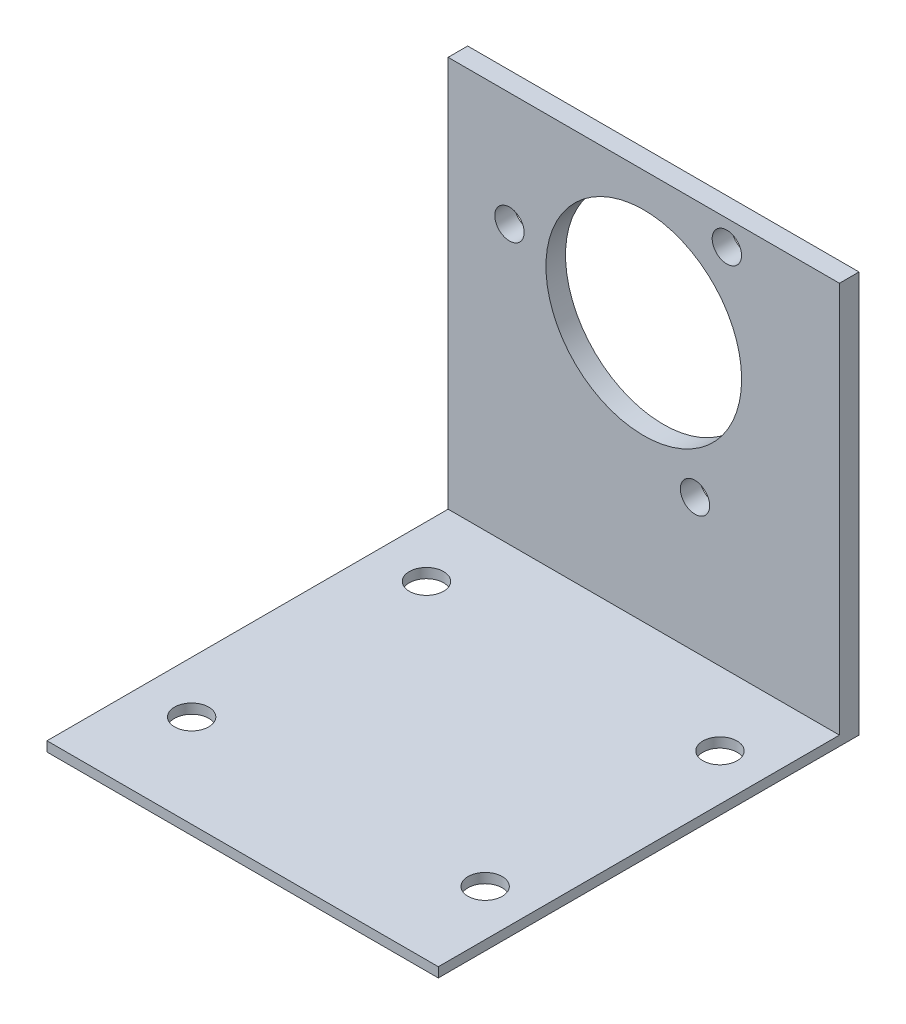
SolidWorks part; units mm, degrees
ref_plane "Front Plane" through (0, 0, 0) normal (0, 0, 1) x (1, 0, 0)
ref_plane "Top Plane" through (0, 0, 0) normal (0, 1, 0) x (1, 0, 0)
ref_plane "Right Plane" through (0, 0, 0) normal (1, 0, 0) x (0, 0, -1)
sketch "Sketch1" plane through (0, 0, 0) normal (0, 1, 0) x (1, 0, 0)
  line L0 (-20, 19.5) -> (20, 19.5)
  line L1 (-20, -21.5) -> (20, -21.5)
  line L2 (-20, -21.5) -> (-20, 21.5)
  line L3 (-20, 21.5) -> (20, 21.5)
  line L4 (20, -21.5) -> (20, 21.5)
  line L5 (-20, -21.5) -> (20, 21.5) construction
  line L6 (-20, 21.5) -> (20, -21.5) construction
  circle A7 centre (-14.7151, 12) radius 1.75
  circle A8 centre (15.2849, 12) radius 1.75
  circle A9 centre (-14.7151, -12) radius 1.75
  circle A10 centre (15.2849, -12) radius 1.75
  point P0 (0, 0)
  dimension "D4" = 30
  dimension "D5" = 3.5
  dimension "D6" = 3.5
  dimension "D7" = 24
  dimension "D8" = 9.5
  dimension "D9" = 5.2849
  dimension "D10" = 3.5
  dimension "D12" = 3.5
  dimension "D1" = 2
  dimension "D2" = 40
  dimension "D3" = 43
  dimension "D11" = 9.5
extrude "Boss-Extrude1" add sketch "Sketch1" against normal blind 1
sketch "Sketch4" plane through (0, 0, 0) normal (0, 1, 0) x (1, 0, 0)
  line L1 (-20, -21.5) -> (-20, 21.5) construction
  line L2 (20, -21.5) -> (20, 21.5) construction
  line L5 (-20, 21.5) -> (20, 21.5)
  line L6 (-20, 21.5) -> (-20, 19.5)
  line L7 (-20, 19.5) -> (20, 19.5)
  line L8 (-20, -21.5) -> (20, -21.5)
  line L9 (20, -21.5) -> (20, 21.5)
  line L10 (20, 21.5) -> (-20, 21.5)
  line L11 (-20, 21.5) -> (-20, -21.5)
  line L12 (-20, -21.5) -> (20, -21.5)
  line L13 (20, -21.5) -> (20, 12.2)
  line L15 (-20, 12.2) -> (-20, -21.5)
  line L16 (20, 21.5) -> (20, 19.5)
  line M13 (20, -21.5) -> (20, 21.5)
  line M14 (20, 21.5) -> (-20, 21.5)
  line M15 (-20, 21.5) -> (-20, -21.5)
  dimension "D1" = 2
  dimension "D2" = 0
extrude "Boss-Extrude2" add sketch "Sketch4" along normal blind 40 contours L7 M15 M13 M14
sketch "Sketch5" plane through (0, 0, -19.5) normal (0, 0, 1) x (1, 0, 0)
  line L0 (-20, 40) -> (20, -1) construction
  line L1 (-20, -1) -> (20, 40) construction
  line L2 (0, 26.5) -> (0, 40) construction
  line L5 (-20, 40) -> (20, 40) construction
  circle A0 centre (0, 26.5) radius 13.8564
  circle A2 centre (8.492, 37.4493) radius 1.5
  circle A3 centre (-13.7283, 28.3796) radius 1.5
  circle A4 centre (5.2364, 13.6711) radius 1.5
  circle A5 centre (0, 26.5) radius 10
  point P13 (0, 26.5)
  point P18 (0, 19.5)
  dimension "D2" = 24
  dimension "D3" = 24
  dimension "D4" = 13.5
  dimension "D1" = 24
extrude "Cut-Extrude1" cut sketch "Sketch5" against normal blind 24 contours A5 | A0 A3 | A0 A3 | A0 A4 | A0 A2 | A0 A2
